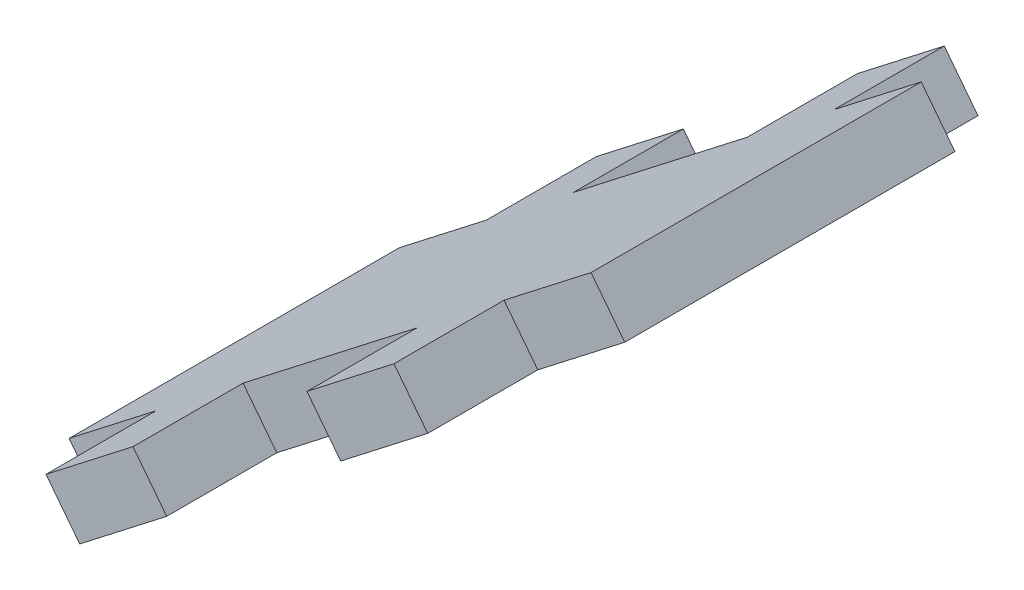
SolidWorks part; units mm, degrees
ref_plane "Front Plane" through (0, 0, 0) normal (0, 0, 1) x (1, 0, 0)
ref_plane "Top Plane" through (0, 0, 0) normal (0, 1, 0) x (1, 0, 0)
ref_plane "Right Plane" through (0, 0, 0) normal (1, 0, 0) x (0, 0, -1)
sketch "Sketch1" plane through (0, 0, 0) normal (0, 0, 1) x (1, 0, 0)
  line L0 (-134.3426, 282.0077) -> (-136.2878, 284.5171)
  line L1 (-136.2878, 284.5171) -> (-106.1751, 307.8588)
  line L2 (-106.1751, 307.8588) -> (-104.2299, 305.3494)
  line L3 (-104.2299, 305.3494) -> (-134.3426, 282.0077)
  dimension "D1" = 3.175
  dimension "D2" = 38.1
extrude "Boss-Extrude1" add sketch "Sketch1" against normal blind 31.75 contours L1 L2 L3 L0
sketch "Sketch2" plane through (-188.9191, 243.72, 0) normal (-0.6126, 0.7904, 0) x (0.7904, 0.6126, 0)
  line L1 (66.5917, 31.75) -> (72.9417, 31.75)
  line L2 (66.5917, 31.75) -> (66.5917, 25.4)
  line L3 (66.5917, 25.4) -> (72.9417, 25.4)
  line L4 (72.9417, 31.75) -> (72.9417, 25.4)
  line L5 (66.5917, 31.75) -> (104.6917, 31.75) construction
  line L6 (104.6917, 31.75) -> (98.3417, 31.75)
  line L7 (104.6917, 31.75) -> (104.6917, 25.4)
  line L8 (104.6917, 25.4) -> (98.3417, 25.4)
  line L9 (98.3417, 31.75) -> (98.3417, 25.4)
  line L10 (79.2917, 31.75) -> (91.9917, 31.75)
  line L11 (79.2917, 31.75) -> (79.2917, 25.4)
  line L12 (79.2917, 25.4) -> (91.9917, 25.4)
  line L13 (91.9917, 31.75) -> (91.9917, 25.4)
  line L15 (66.5917, 0) -> (72.9417, 0)
  line L16 (66.5917, 0) -> (66.5917, 6.35)
  line L17 (66.5917, 6.35) -> (72.9417, 6.35)
  line L18 (72.9417, 0) -> (72.9417, 6.35)
  line L19 (66.5917, 0) -> (104.6917, 0) construction
  line L20 (79.2917, 0) -> (91.9917, 0)
  line L21 (79.2917, 0) -> (79.2917, 6.35)
  line L22 (79.2917, 6.35) -> (91.9917, 6.35)
  line L23 (91.9917, 0) -> (91.9917, 6.35)
  line L25 (104.6917, 0) -> (98.3417, 0)
  line L26 (104.6917, 0) -> (104.6917, 6.35)
  line L27 (104.6917, 6.35) -> (98.3417, 6.35)
  line L28 (98.3417, 0) -> (98.3417, 6.35)
  dimension "D1" = 6.35
  dimension "D2" = 6.35
  dimension "D3" = 6.35
  dimension "D4" = 6.35
  dimension "D5" = 6.35
  dimension "D6" = 6.35
  dimension "D7" = 6.35
  dimension "D8" = 6.35
  dimension "D9" = 6.35
  dimension "D10" = 6.35
  dimension "D11" = 6.35
  dimension "D12" = 6.35
  dimension "D13" = 6.35
  dimension "D14" = 6.35
extrude "Cut-Extrude1" cut sketch "Sketch2" against normal through all
